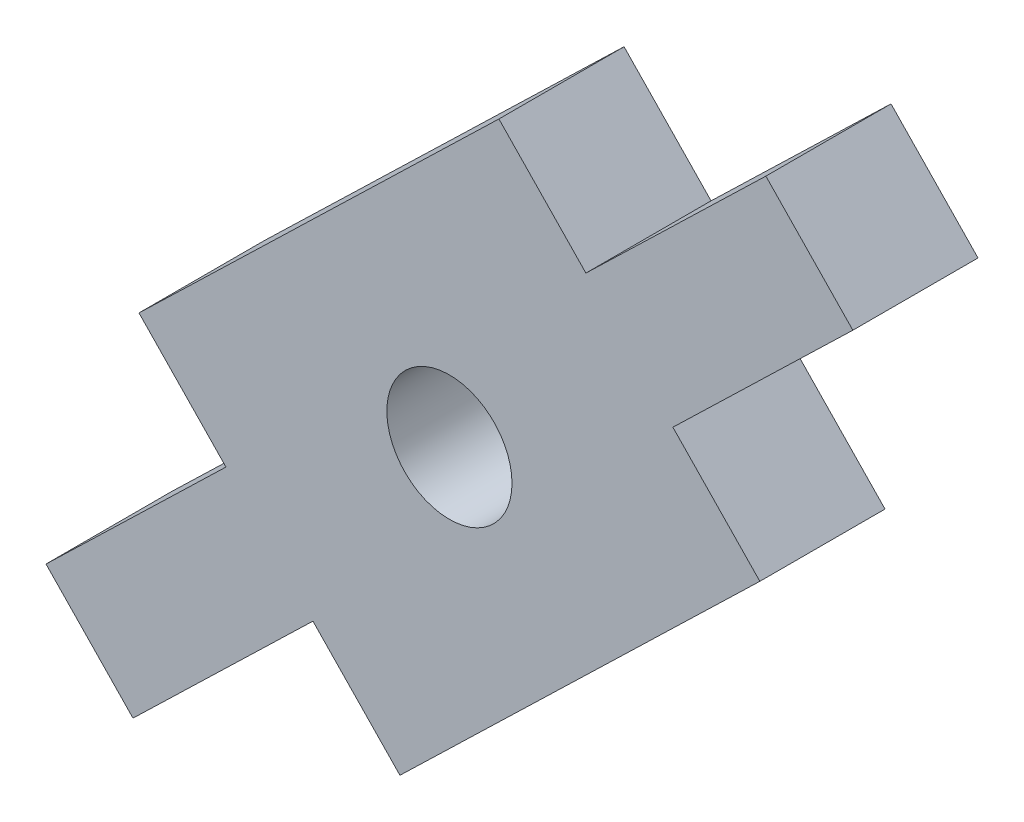
SolidWorks part; units mm, degrees
ref_plane "Plan de face" through (0, 0, 0) normal (0, 0, 1) x (1, 0, 0)
ref_plane "Plan de dessus" through (0, 0, 0) normal (0, 1, 0) x (1, 0, 0)
ref_plane "Plan de droite" through (0, 0, 0) normal (1, 0, 0) x (0, 0, -1)
sketch "Esquisse15" plane through (0, 0, 0) normal (0, 0, 1) x (1, 0, 0)
  line L0 (175.0792, -50.614) -> (183.707, -42.2738)
  line L1 (175.0792, -50.614) -> (172.9941, -48.4571)
  line L2 (183.707, -42.2738) -> (181.6219, -40.1168)
  line L3 (168.824, -44.1432) -> (177.4518, -35.8029)
  line L4 (166.5951, -50.4703) -> (170.909, -46.3001)
  line L5 (166.5951, -50.4703) -> (168.6802, -52.6272)
  line L6 (183.8508, -33.7897) -> (185.9359, -35.9467)
  line L7 (168.6802, -52.6272) -> (172.9941, -48.4571)
  line L8 (179.5369, -37.9599) -> (183.8508, -33.7897)
  line L9 (181.6219, -40.1168) -> (185.9359, -35.9467)
  line L10 (170.909, -46.3001) -> (168.824, -44.1432)
  line L11 (179.5369, -37.9599) -> (177.4518, -35.8029)
  line L12 (167.6376, -51.5487) -> (184.8933, -34.8682) construction
  line L13 (179.3931, -46.4439) -> (173.1379, -39.973) construction
  circle A0 centre (176.2655, -43.2085) radius 1.5
  dimension "D4" = 3
  dimension "D1" = 12
  dimension "D2" = 24
  dimension "D3" = 6
  dimension "D5" = 3
  dimension "D6" = 3
  dimension "D7" = 3
extrude "Boss.-Extru.15" add sketch "Esquisse15" along normal blind 3 separate body
